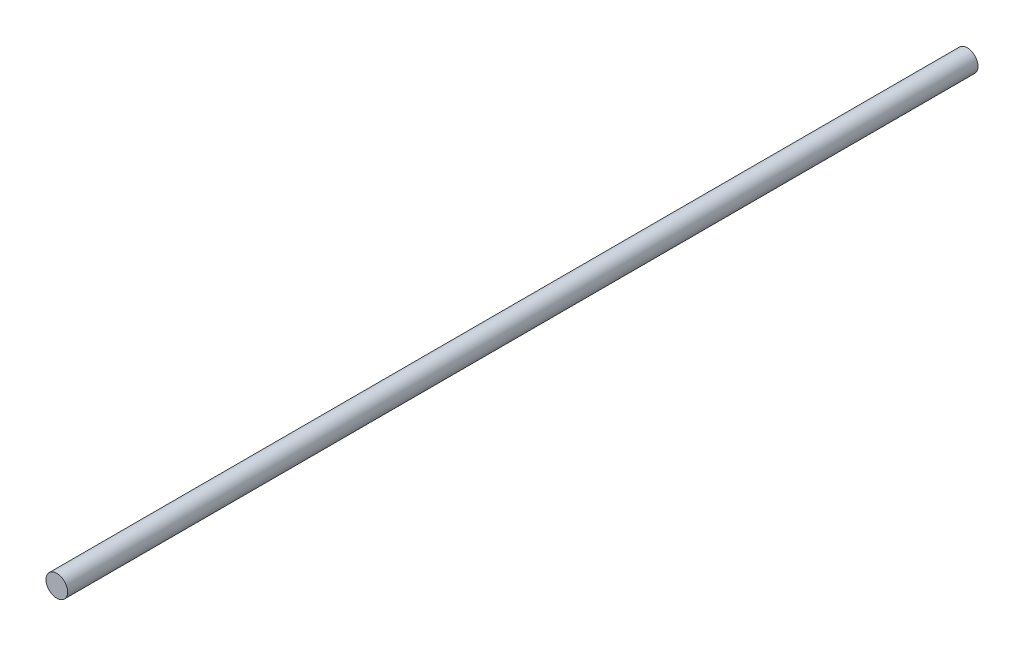
SolidWorks part; units mm, degrees
ref_plane "Front" through (0, 0, 0) normal (0, 0, 1) x (1, 0, 0)
ref_plane "Top" through (0, 0, 0) normal (0, 1, 0) x (1, 0, 0)
ref_plane "Right" through (0, 0, 0) normal (1, 0, 0) x (0, 0, -1)
sketch "Sketch1" plane through (0, 0, 0) normal (0, 0, 1) x (1, 0, 0)
  circle A0 centre (0, 0) radius 4
  dimension "D1" = 8
extrude "Boss-Extrude1" add sketch "Sketch1" along normal blind 337
equation "\"D1@Sketch1\"=8"
equation "\"base-xwidth\"= 455mm"
equation "\"base-yheight\"= 533mm"
equation "\"base-zdepth\" = 377mm"
equation "\"D1@Boss-Extrude1\"=\"base-zdepth\"-40mm"
